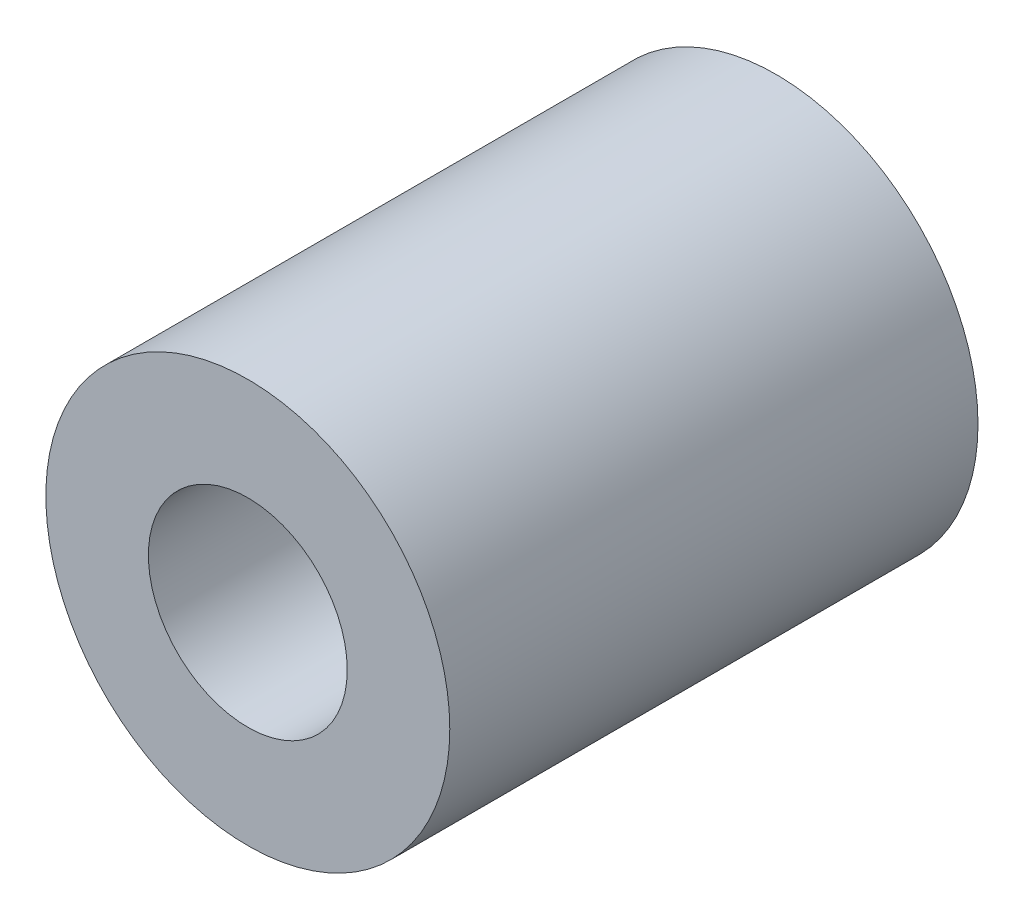
SolidWorks part; units mm, degrees
ref_plane "Alzado" through (0, 0, 0) normal (0, 0, 1) x (1, 0, 0)
ref_plane "Planta" through (0, 0, 0) normal (0, 1, 0) x (1, 0, 0)
ref_plane "Vista lateral" through (0, 0, 0) normal (1, 0, 0) x (0, 0, -1)
sketch "Croquis1" plane through (0, 0, 0) normal (0, 0, 1) x (1, 0, 0)
  circle A0 centre (0, 0) radius 3.25
  dimension "D1" = 6.5
extrude "Saliente-Extruir1" add sketch "Croquis1" along normal blind 8.5
sketch "Croquis2" plane through (0, 0, 8.5) normal (0, 0, 1) x (1, 0, 0)
  circle A0 centre (0, 0) radius 1.6
  dimension "D1" = 3.2
extrude "Cortar-Extruir1" cut sketch "Croquis2" against normal blind 9
